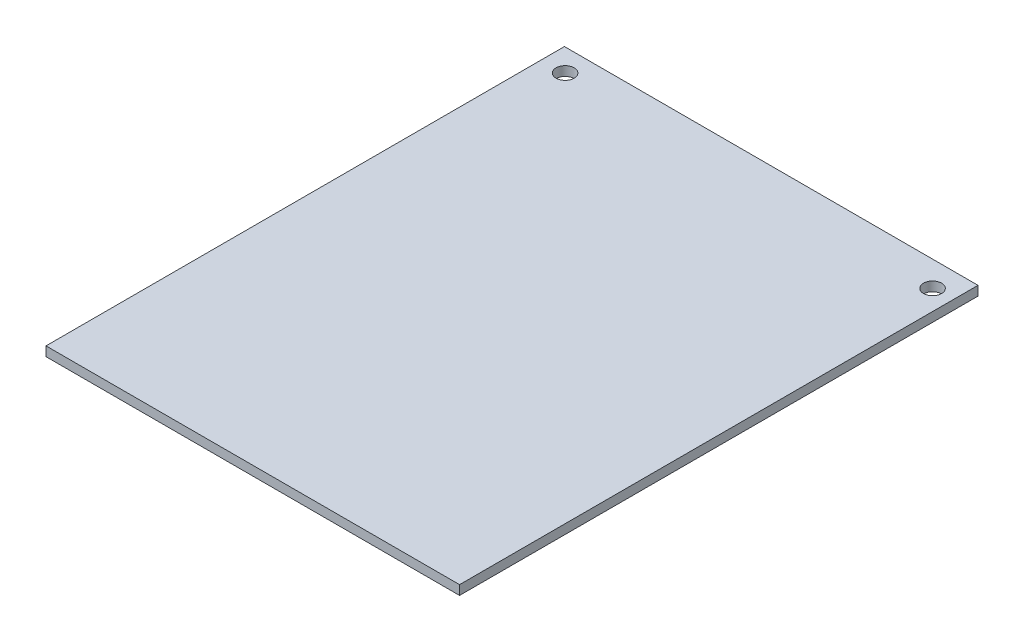
SolidWorks part; units mm, degrees
ref_plane "Front Plane" through (0, 0, 0) normal (0, 0, 1) x (1, 0, 0)
ref_plane "Top Plane" through (0, 0, 0) normal (0, 1, 0) x (1, 0, 0)
ref_plane "Right Plane" through (0, 0, 0) normal (1, 0, 0) x (0, 0, -1)
sketch "Sketch1" plane through (0, 0, 0) normal (0, 1, 0) x (1, 0, 0)
  line L1 (-42.0326, 37.6593) -> (31.2274, 37.6593)
  line L2 (-42.0326, 37.6593) -> (-42.0326, -54.1807)
  line L3 (-42.0326, -54.1807) -> (31.2274, -54.1807)
  line L4 (31.2274, 37.6593) -> (31.2274, -54.1807)
  circle A0 centre (27.6674, 33.1693) radius 1.6
  circle A1 centre (-37.9126, 33.6593) radius 1.6
  dimension "D3" = 3.2
  dimension "D1" = 91.84
  dimension "D2" = 73.26
  dimension "D4" = 3.56
  dimension "D5" = 4.49
  dimension "D6" = 4.12
  dimension "D7" = 4
extrude "Boss-Extrude1" add sketch "Sketch1" along normal blind 1.66
